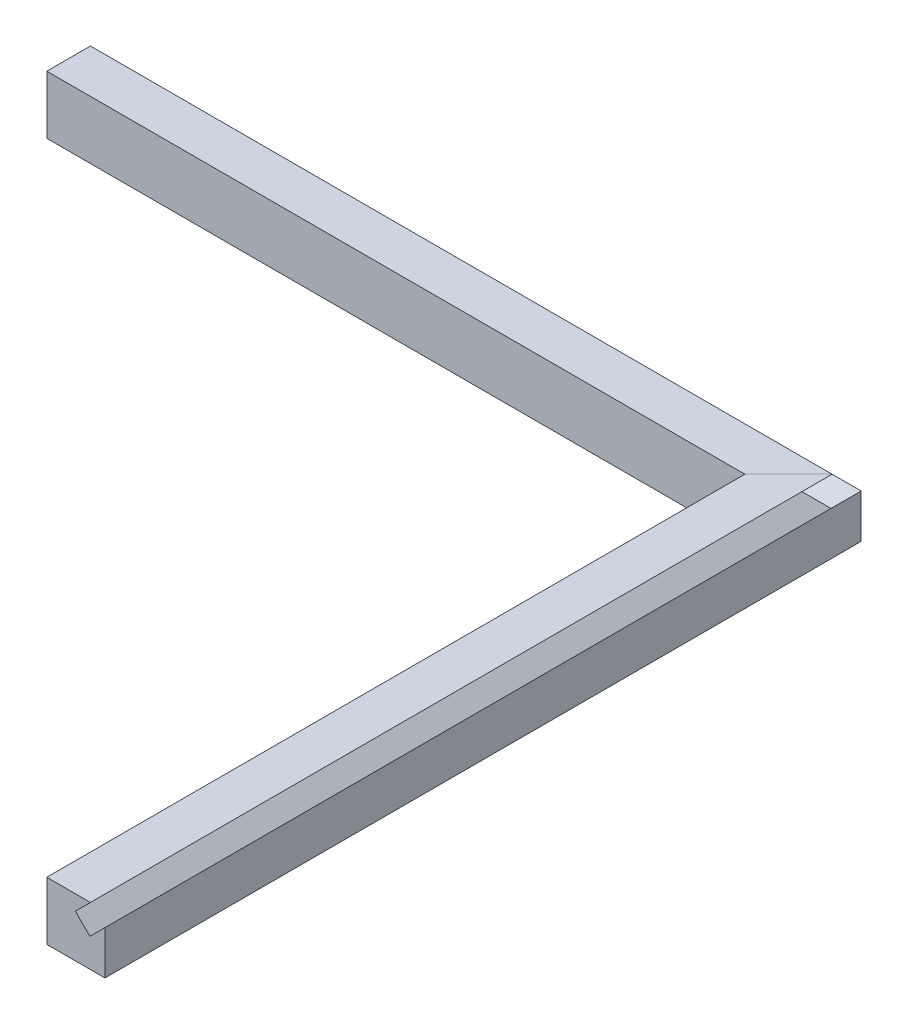
SolidWorks part; units mm, degrees
ref_plane "Front Plane" through (0, 0, 0) normal (0, 0, 1) x (1, 0, 0)
ref_plane "Top Plane" through (0, 0, 0) normal (0, 1, 0) x (1, 0, 0)
ref_plane "Right Plane" through (0, 0, 0) normal (1, 0, 0) x (0, 0, -1)
sketch "Sketch3" plane through (0, 0, 0) normal (0, 0, 1) x (1, 0, 0)
  line L0 (0, -4.4428) -> (0, -24.4428)
  line L1 (0, -24.4428) -> (20, -24.4428)
  line L2 (20, -24.4428) -> (20, -9.4428)
  line L3 (20, -9.4428) -> (14.8117, -14.6311)
  line L4 (14.8117, -14.6311) -> (9.8117, -9.6311)
  line L5 (9.8117, -9.6311) -> (15, -4.4428)
  line L6 (0, -4.4428) -> (15, -4.4428)
  point P8 (47.8057, 33.0054)
  point P9 (29.4284, 1.4193)
  point P10 (63.168, 2.7115)
  dimension "D1" = 45
  dimension "D2" = 20
  dimension "D3" = 15
  dimension "D4" = 15
sketch "Sketch4" plane through (0, 0, 0) normal (0, 1, 0) x (1, 0, 0)
  line L0 (0, 0) -> (0, 240)
  line L1 (0, 240) -> (-240, 240)
  point P3 (0, 26.5988)
  point P5 (254.4488, 254.4488)
  point P6 (0, 0)
  point P7 (-257.4517, 240)
  dimension "D1" = 240
sweep "Sweep2" add profiles "Sketch3" path "Sketch4"
